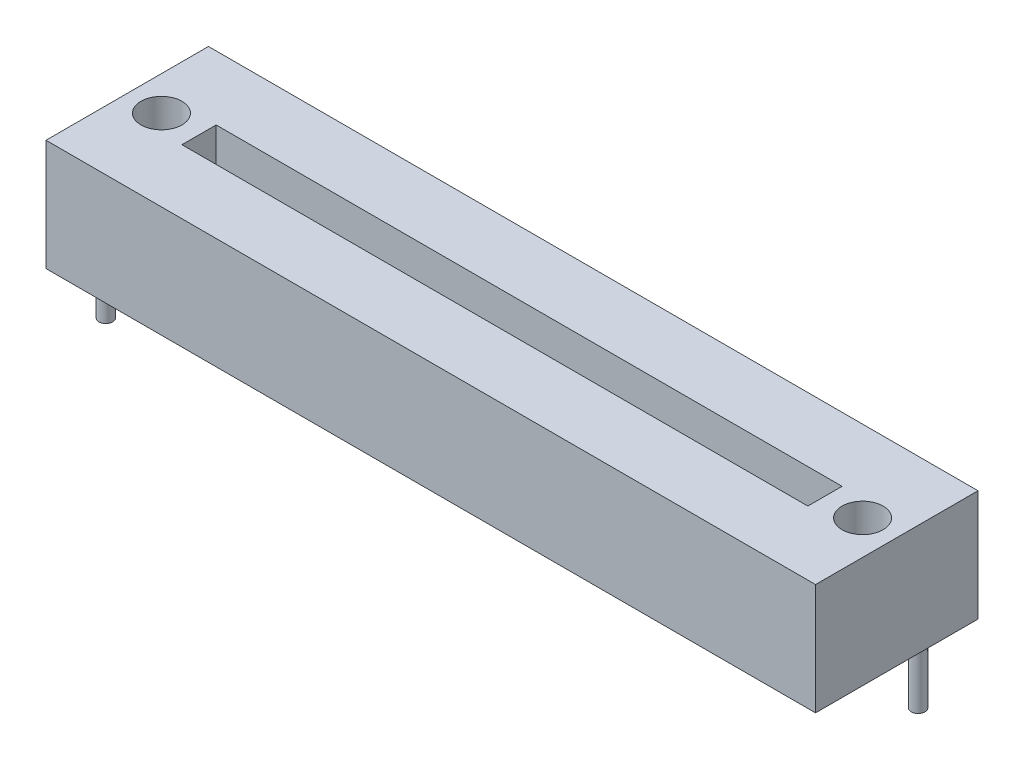
SolidWorks part; units mm, degrees
ref_plane "Front Plane" through (0, 0, 0) normal (0, 0, 1) x (1, 0, 0)
ref_plane "Top Plane" through (0, 0, 0) normal (0, 1, 0) x (1, 0, 0)
ref_plane "Right Plane" through (0, 0, 0) normal (1, 0, 0) x (0, 0, -1)
sketch "Sketch1" plane through (0, 0, 0) normal (0, 1, 0) x (1, 0, 0)
  line L1 (-22.5, -4.75) -> (22.5, -4.75)
  line L2 (-22.5, -4.75) -> (-22.5, 4.75)
  line L3 (-22.5, 4.75) -> (22.5, 4.75)
  line L4 (22.5, -4.75) -> (22.5, 4.75)
  line L5 (-22.5, -4.75) -> (22.5, 4.75) construction
  line L6 (-22.5, 4.75) -> (22.5, -4.75) construction
  line L7 (-18.3, -1) -> (18.3, -1)
  line L8 (-18.3, -1) -> (-18.3, 1)
  line L9 (-18.3, 1) -> (18.3, 1)
  line L10 (18.3, -1) -> (18.3, 1)
  line L11 (-18.3, -1) -> (18.3, 1) construction
  line L12 (-18.3, 1) -> (18.3, -1) construction
  point P0 (0, 0)
  point P6 (0, 0)
  dimension "D1" = 45
  dimension "D2" = 9.5
  dimension "D3" = 2
  dimension "D4" = 36.6
extrude "Boss-Extrude1" add sketch "Sketch1" along normal blind 6.5
sketch "Sketch2" plane through (0, 0, 0) normal (0, -1, 0) x (1, 0, 0)
  line L0 (22.5, 4.75) -> (22.5, -4.75) construction
  line L1 (22.5, -4.75) -> (-22.5, -4.75) construction
  line L2 (-22.5, -4.75) -> (-22.5, 4.75) construction
  line L3 (-22.5, 4.75) -> (22.5, 4.75) construction
  line L4 (22.5, 4.75) -> (22.5, -4.75)
  line L5 (22.5, -4.75) -> (-22.5, -4.75)
  line L6 (-22.5, -4.75) -> (-22.5, 4.75)
  line L7 (-22.5, 4.75) -> (22.5, 4.75)
extrude "Boss-Extrude2" add sketch "Sketch2" against normal blind 2
sketch "Sketch3" plane through (0, 6.5, 0) normal (0, 1, 0) x (1, 0, 0)
  line L0 (-20.5, 0) -> (20.5, 0) construction
  circle A0 centre (-20.5, 0) radius 1
  circle A1 centre (20.5, 0) radius 1
  point P0 (-20.5, 0)
  point P1 (20.5, 0)
  point P2 (0, 0)
  point P9 (-20.5, 0)
  point P13 (20.5, 0)
  dimension "D2" = 2
  dimension "D1" = 41
hole_wizard "M2 Clearance Hole1" positions "Sketch3" profile "Sketch4" hole size "M2" standard "ANSI Metric" end condition through all
sketch "Sketch4" plane through (20.5, 6.5, 0) normal (1, 0, 0) x (0, 0, 1)
  line L0 (0, 0) -> (0, 6.5)
  line L1 (0, 6.5) -> (1.2, 6.5)
  line L2 (1.2, 6.5) -> (1.2, 0)
  line L5 (1.2, 0) -> (0, 0)
  line L11 (0, -6.35) -> (0, 107.95) construction
  dimension "Thru Hole Dia." = 2.4
  dimension "Thru Hole Depth" = 6.5
sketch "Sketch5" plane through (0, 0, 0) normal (0, -1, 0) x (1, 0, 0)
  line L1 (-21.75, -2) -> (21.75, -2) construction
  line L2 (-21.75, -2) -> (-21.75, 2) construction
  line L3 (-21.75, 2) -> (21.75, 2) construction
  line L4 (21.75, -2) -> (21.75, 2) construction
  line L5 (-21.75, -2) -> (21.75, 2) construction
  line L6 (-21.75, 2) -> (21.75, -2) construction
  circle A0 centre (-21.75, 2) radius 0.4
  circle A1 centre (-21.75, -2) radius 0.4
  circle A2 centre (21.75, -2) radius 0.4
  point P0 (0, 0)
  dimension "D3" = 0.8
  dimension "D1" = 43.5
  dimension "D2" = 4
extrude "Boss-Extrude3" add sketch "Sketch5" along normal blind 3.5
